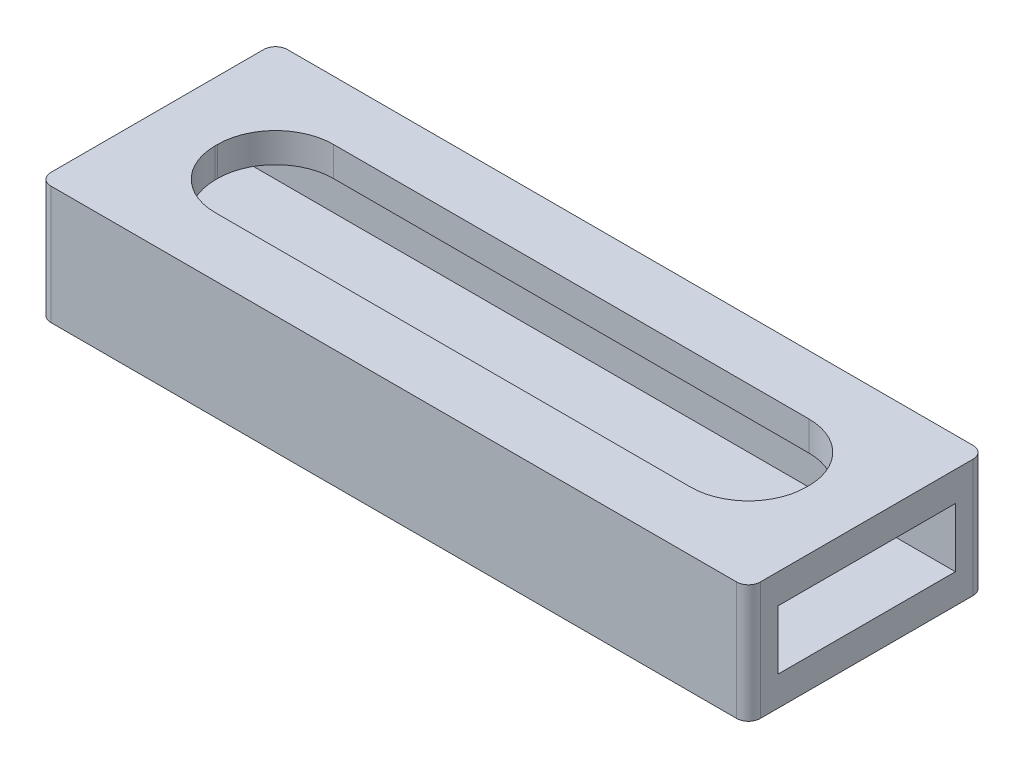
SolidWorks part; units mm, degrees
ref_plane "Front Plane" through (0, 0, 0) normal (0, 0, 1) x (1, 0, 0)
ref_plane "Top Plane" through (0, 0, 0) normal (0, 1, 0) x (1, 0, 0)
ref_plane "Right Plane" through (0, 0, 0) normal (1, 0, 0) x (0, 0, -1)
sketch "Sketch1" plane through (0, 0, 0) normal (0, 1, 0) x (1, 0, 0)
  line L1 (0, 0) -> (76.2, 0)
  line L2 (0, 0) -> (0, 25.4)
  line L3 (0, 25.4) -> (76.2, 25.4)
  line L4 (76.2, 0) -> (76.2, 25.4)
  dimension "D1" = 25.4
  dimension "D2" = 76.2
extrude "Boss-Extrude1" add sketch "Sketch1" along normal blind 12.7
sketch "Sketch2" plane through (76.2, 0, 0) normal (1, 0, 0) x (0, 0, -1)
  line L1 (3.175, 3.175) -> (22.225, 3.175)
  line L2 (3.175, 3.175) -> (3.175, 9.525)
  line L3 (3.175, 9.525) -> (22.225, 9.525)
  line L4 (22.225, 3.175) -> (22.225, 9.525)
  line L5 (0, 12.7) -> (0, 0) construction
  line L6 (0, 12.7) -> (25.4, 12.7) construction
  dimension "D1" = 19.05
  dimension "D2" = 3.175
  dimension "D3" = 6.35
  dimension "D4" = 3.175
extrude "Cut-Extrude1" cut sketch "Sketch2" against normal through all
sketch "Sketch3" plane through (0, 12.7, 0) normal (0, 1, 0) x (1, 0, 0)
  line L0 (76.2, 25.4) -> (0, 25.4) construction
  line L1 (12.573, 6.35) -> (63.627, 6.35)
  line L2 (6.35, 12.573) -> (6.35, 12.827)
  line L3 (12.573, 19.05) -> (63.627, 19.05)
  line L4 (69.85, 12.573) -> (69.85, 12.827)
  line L5 (0, 25.4) -> (0, 0) construction
  arc A0 (63.627, 19.05) -> (69.85, 12.827) centre (63.627, 12.827) cw
  arc A1 (69.85, 12.573) -> (63.627, 6.35) centre (63.627, 12.573) cw
  arc A2 (12.573, 6.35) -> (6.35, 12.573) centre (12.573, 12.573) cw
  arc A3 (6.35, 12.827) -> (12.573, 19.05) centre (12.573, 12.827) cw
  point P10 (69.85, 19.05)
  point P13 (69.85, 6.35)
  point P16 (6.35, 6.35)
  dimension "D5" = 6.223
  dimension "D1" = 63.5
  dimension "D2" = 6.35
  dimension "D3" = 12.7
  dimension "D4" = 6.35
extrude "Cut-Extrude2" cut sketch "Sketch3" against normal blind 3.175
fillet "Fillet1" radius 1.27 4 edges at (0, 6.35, 0) (76.2, 6.35, 0) (76.2, 6.35, -25.4) (0, 6.35, -25.4)
